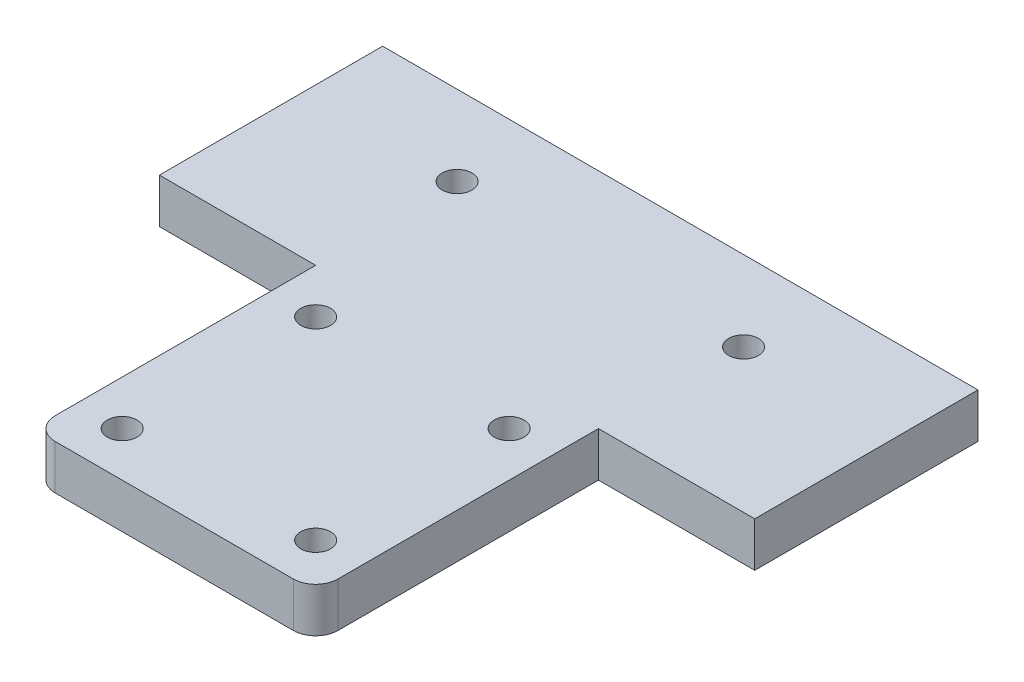
SolidWorks part; units mm, degrees
ref_plane "Front Plane" through (0, 0, 0) normal (0, 0, 1) x (1, 0, 0)
ref_plane "Top Plane" through (0, 0, 0) normal (0, 1, 0) x (1, 0, 0)
ref_plane "Right Plane" through (0, 0, 0) normal (1, 0, 0) x (0, 0, -1)
sketch "Sketch1" plane through (0, 0, 0) normal (0, 1, 0) x (1, 0, 0)
  line L1 (0, 0) -> (38, 0)
  line L2 (0, 0) -> (0, 38)
  line L3 (0, 38) -> (38, 38)
  line L4 (38, 0) -> (38, 38)
  dimension "D1" = 38
  dimension "D2" = 38
extrude "Boss-Extrude1" add sketch "Sketch1" along normal blind 6
sketch "Sketch2" plane through (0, 6, 0) normal (0, 1, 0) x (1, 0, 0)
  line L0 (38, 38) -> (0, 38) construction
  line L1 (0, 38) -> (0, 0) construction
  circle A0 centre (6, 32) radius 2
  point P2 (0, 0)
  dimension "D1" = 4
  dimension "D2" = 6
  dimension "D3" = 6
extrude "Cut-Extrude1" cut sketch "Sketch2" against normal through all
pattern_linear "LPattern1" count 2 spacing 26 along (1, 0, 0) count 2 spacing 26 along (0, 0, 1) of "Cut-Extrude1"
fillet "Fillet1" radius 3 2 edges at (38, 3, 0) (0, 3, 0)
sketch "Sketch3" plane through (0, 0, 0) normal (0, 1, 0) x (1, 0, 0)
  line L0 (0, 38) -> (-21, 38)
  line L1 (-21, 38) -> (-21, 68)
  line L2 (-21, 68) -> (59, 68)
  line L3 (59, 68) -> (59, 38)
  line L4 (59, 38) -> (38, 38)
  line L5 (38, 38) -> (0, 38)
  line L6 (0, 38) -> (0, 3) construction
  dimension "D1" = 80
  dimension "D2" = 30
  dimension "D3" = 21
extrude "Boss-Extrude2" add sketch "Sketch3" along normal blind 6
sketch "Sketch4" plane through (0, 6, 0) normal (0, 1, 0) x (1, 0, 0)
  line L0 (-21, 68) -> (-21, 38) construction
  line L2 (-21, 38) -> (0, 38) construction
  line L3 (59, 68) -> (-21, 68) construction
  circle A0 centre (-0.25, 57.25) radius 2
  circle A1 centre (38.25, 57.25) radius 2
  dimension "D1" = 38.5
  dimension "D3" = 19.25
  dimension "D4" = 4
  dimension "D5" = 4
  dimension "D6" = 10.75
  dimension "D2" = 20.75
extrude "Cut-Extrude2" cut sketch "Sketch4" against normal through all
